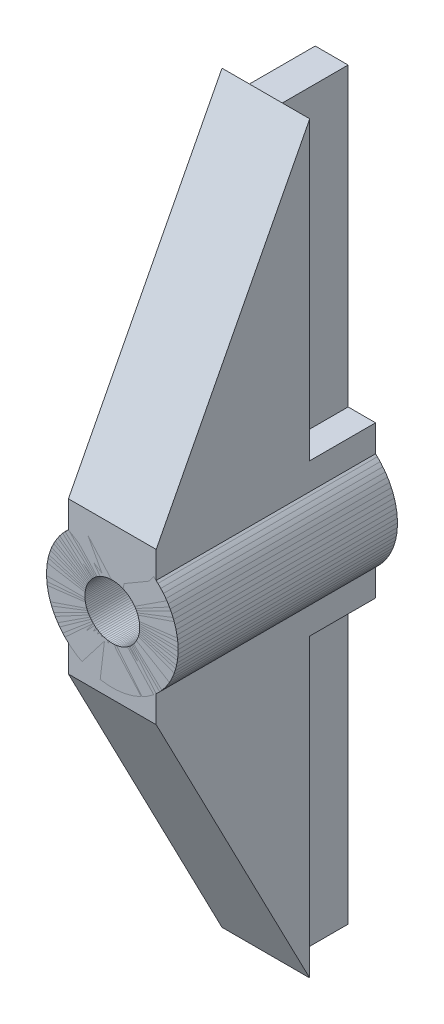
SolidWorks part; units mm, degrees
ref_plane "Front Plane" through (0, 0, 0) normal (0, 0, 1) x (1, 0, 0)
ref_plane "Top Plane" through (0, 0, 0) normal (0, 1, 0) x (1, 0, 0)
ref_plane "Right Plane" through (0, 0, 0) normal (1, 0, 0) x (0, 0, -1)
other "Configuration Table"
sketch "Sketch1" plane through (0, 0, 0) normal (0, 0, 1) x (1, 0, 0)
  circle A0 centre (0, 0) radius 2.5
  circle A1 centre (0, 0) radius 6
  dimension "D1" = 5
  dimension "D2" = 12
extrude "Boss-Extrude1" add sketch "Sketch1" along normal blind 20
sketch "Sketch2" plane through (0, 0, 0) normal (1, 0, 0) x (0, 0, -1)
  line L0 (-20, 6.9198) -> (-20, 3.9198)
  line L2 (-20, 3.9198) -> (0, 3.9198)
  line L3 (-20, 6) -> (-20, -6) construction
  line L5 (0, 3.9198) -> (0, 33.9198)
  line L6 (-20, 6.9198) -> (-6, 33.9198)
  line L7 (-6, 33.9198) -> (0, 33.9198)
  dimension "D1" = 30
  dimension "D2" = 6
  dimension "D3" = 3
extrude "Boss-Extrude2" add sketch "Sketch2" along normal mid plane 8
sketch "Sketch3" plane through (0, 33.9198, 0) normal (0, 1, 0) x (1, 0, 0)
  line L0 (-4, 0) -> (-1.5, 0)
  line L1 (4, 0) -> (-4, 0) construction
  line L2 (-1.5, 0) -> (-1.5, -6)
  line L3 (4, -6) -> (-4, -6) construction
  line L4 (-1.5, -6) -> (-4, -6)
  line L5 (-4, -6) -> (-4, 0)
  line L6 (4, 0) -> (1.5, 0)
  line L7 (1.5, 0) -> (1.5, -6)
  line L8 (1.5, -6) -> (4, -6)
  line L9 (4, -6) -> (4, 0)
  dimension "D1" = 2.5
extrude "Cut-Extrude1" cut sketch "Sketch3" against normal up to vertex (27 mm away) up to point (4, 6.9198, 20)
move or copy body "Body-Move/Copy1" bodies to move or copy 104 copy yes number of copies 1 rotation origin (0, 0, 0) rotation axis (0, 0, 1) rotation angle 180
